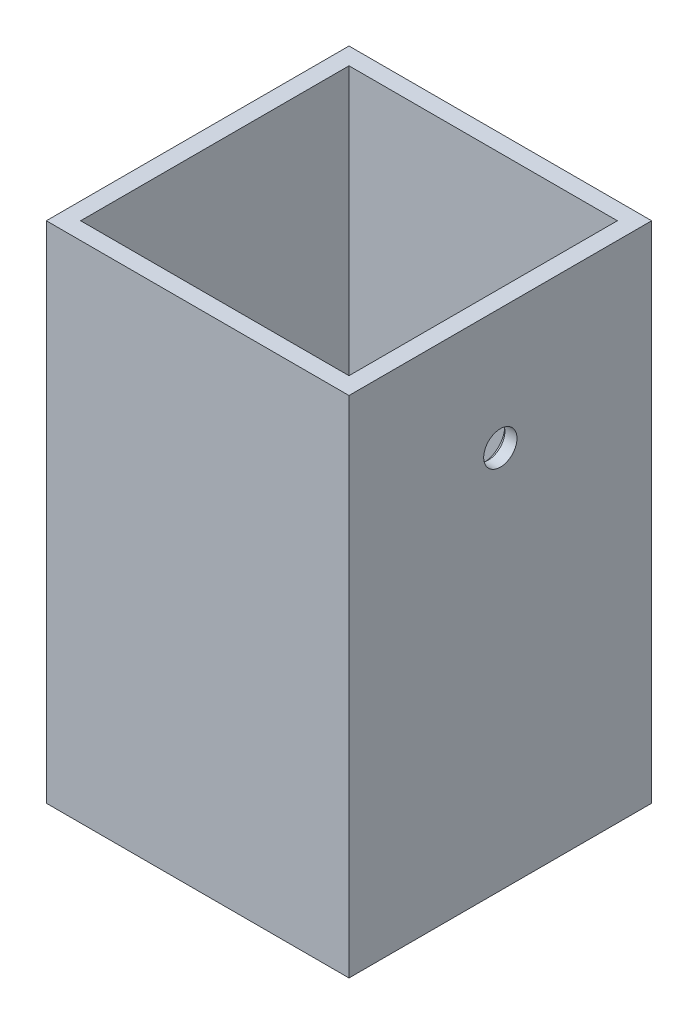
SolidWorks part; units mm, degrees
ref_plane "Front Plane" through (0, 0, 0) normal (0, 0, 1) x (1, 0, 0)
ref_plane "Top Plane" through (0, 0, 0) normal (0, 1, 0) x (1, 0, 0)
ref_plane "Right Plane" through (0, 0, 0) normal (1, 0, 0) x (0, 0, -1)
sketch "Sketch1" plane through (0, 0, 0) normal (0, 1, 0) x (1, 0, 0)
  line L1 (-15, -15) -> (15, -15)
  line L2 (-15, -15) -> (-15, 15)
  line L3 (-15, 15) -> (15, 15)
  line L4 (15, -15) -> (15, 15)
  line L5 (-15, -15) -> (15, 15) construction
  line L6 (-15, 15) -> (15, -15) construction
  point P0 (0, 0)
  dimension "D1" = 30
  dimension "D2" = 30
extrude "Boss-Extrude1" add sketch "Sketch1" along normal blind 50
shell "Shell1" thickness 1.7
sketch "Sketch2" plane through (-15, 0, 0) normal (-1, 0, 0) x (0, 0, 1)
  line L0 (15, 50) -> (15, 0) construction
  line L2 (-15, 0) -> (15, 0) construction
  circle A0 centre (0, 12) radius 1.65
  dimension "D1" = 3.3
  dimension "D2" = 15
  dimension "D3" = 12
extrude "Cut-Extrude1" cut sketch "Sketch2" against normal blind 2
sketch "Sketch3" plane through (15, 0, 0) normal (1, 0, 0) x (0, 0, -1)
  line L0 (-15, 50) -> (-15, 0) construction
  line L1 (-15, 0) -> (15, 0) construction
  circle A0 centre (0, 38) radius 1.65
  dimension "D1" = 3.3
  dimension "D2" = 15
  dimension "D3" = 38
extrude "Cut-Extrude2" cut sketch "Sketch3" against normal blind 2
chamfer "Chamfer1" distance 0.5 angle 45 1 edges at (13.3, 38, 1.65)
chamfer "Chamfer2" distance 0.5 angle 45 1 edges at (-13.3, 12, -1.65)
